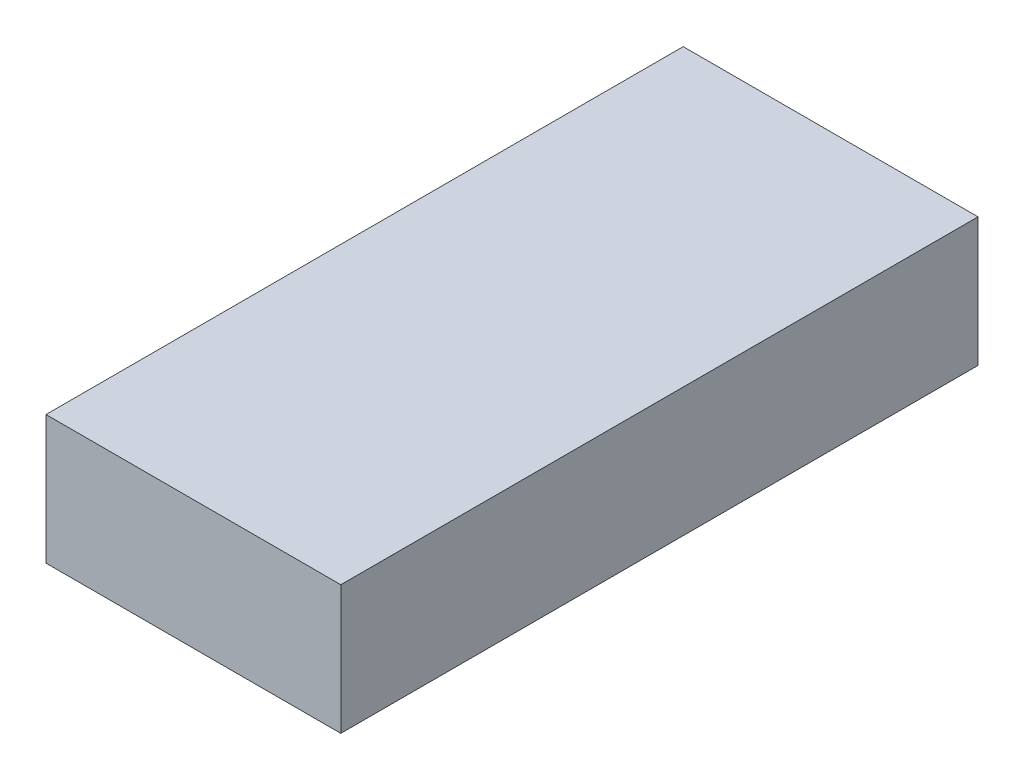
SolidWorks part; units mm, degrees
ref_plane "Front Plane" through (0, 0, 0) normal (0, 0, 1) x (1, 0, 0)
ref_plane "Top Plane" through (0, 0, 0) normal (0, 1, 0) x (1, 0, 0)
ref_plane "Right Plane" through (0, 0, 0) normal (1, 0, 0) x (0, 0, -1)
sketch "Sketch1" plane through (0, 0, 0) normal (0, 1, 0) x (1, 0, 0)
  line L1 (-65.0564, 33.949) -> (-42.1564, 33.949)
  line L2 (-65.0564, 33.949) -> (-65.0564, -15.551)
  line L3 (-65.0564, -15.551) -> (-42.1564, -15.551)
  line L4 (-42.1564, 33.949) -> (-42.1564, -15.551)
  dimension "D1" = 22.9
  dimension "D2" = 49.5
extrude "Boss-Extrude1" add sketch "Sketch1" along normal blind 10
